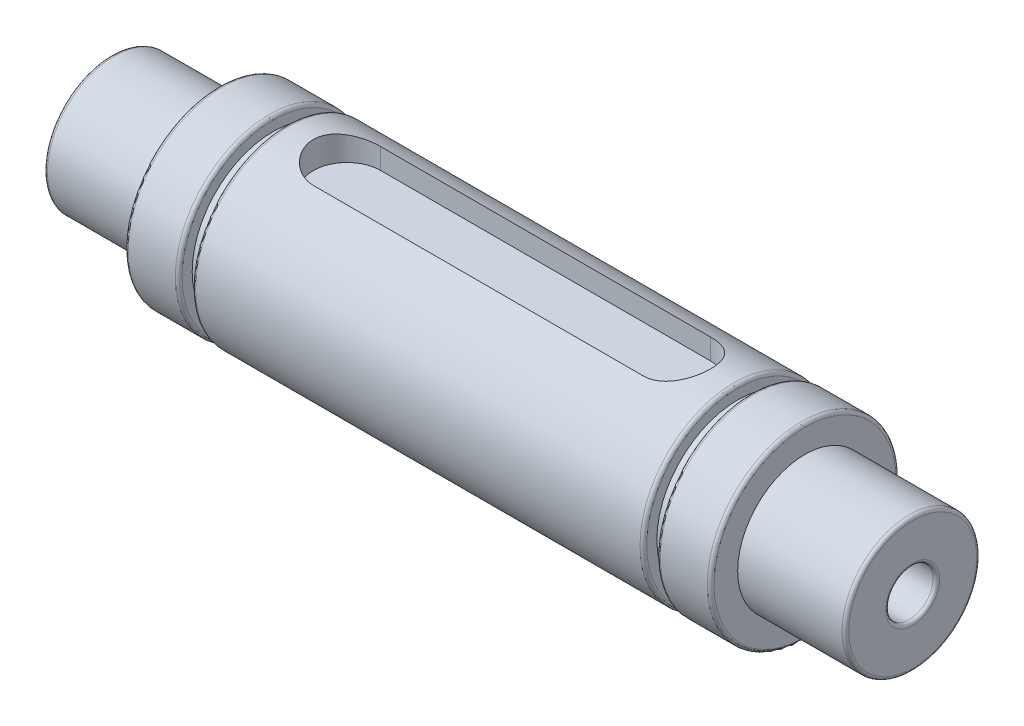
SolidWorks part; units mm, degrees
ref_plane "Front Plane" through (0, 0, 0) normal (0, 0, 1) x (1, 0, 0)
ref_plane "Top Plane" through (0, 0, 0) normal (0, 1, 0) x (1, 0, 0)
ref_plane "Right Plane" through (0, 0, 0) normal (1, 0, 0) x (0, 0, -1)
sketch "Sketch1" plane through (0, 0, 0) normal (0, 1, 0) x (1, 0, 0)
  line L0 (-23.6017, 0) -> (55.1984, 0) construction
sketch "Sketch3" plane through (0, 0, 0) normal (0, 1, 0) x (1, 0, 0)
  line L2 (-29.75, 5) -> (-21.75, 5)
  line L3 (-21.75, 5) -> (-21.75, 7)
  line L5 (21.75, 7) -> (21.75, 5)
  line L6 (21.75, 5) -> (29.75, 5)
  line L9 (-21.75, 7) -> (-17.75, 7)
  line L10 (-17.75, 7) -> (-17.75, 6)
  line L11 (-17.75, 6) -> (-16.75, 6)
  line L12 (-16.75, 6) -> (-16.75, 7)
  line L13 (-16.75, 7) -> (16.75, 7)
  line L14 (16.75, 7) -> (16.75, 6)
  line L15 (16.75, 6) -> (17.75, 6)
  line L16 (17.75, 6) -> (17.75, 7)
  line L17 (17.75, 7) -> (21.75, 7)
  line L18 (29.75, 5) -> (29.75, 1.75)
  line L19 (29.75, 1.75) -> (23.25, 1.75)
  line L20 (23.25, 1.75) -> (23.25, 0)
  line L21 (-29.75, 5) -> (-29.75, 1.75)
  line L22 (-29.75, 1.75) -> (-23.25, 1.75)
  line L23 (-23.25, 1.75) -> (-23.25, 0)
  line L24 (-200023.6017, 0) -> (200055.1984, 0) construction
  line L25 (-23.25, 0) -> (23.25, 0)
  dimension "D1" = 59.5
  dimension "D2" = 7
  dimension "D3" = 8
  dimension "D4" = 5
  dimension "D5" = 1
  dimension "D6" = 4
  dimension "D7" = 1
  dimension "D8" = 1.75
  dimension "D9" = 6.5
revolve "Revolve1" add sketch "Sketch3" angle 360 about L0
fillet "Fillet1" radius 0.25 10 edges at (29.75, 0, 1.75) (-29.75, 0, 1.75) (-29.75, 0, 5) (-21.75, 0, 7) (-16.75, 0, 7) (-17.75, 0, 7) (17.75, 0, 7) (16.75, 0, 7) (21.75, 0, 7) (29.75, 0, 5)
fillet "Fillet2" radius 1.5 2 edges at (-23.25, 0, 1.75) (23.25, 0, 1.75)
ref_plane "Plane1" through (0, 7, 0) normal (0, 1, 0) x (1, 0, 0)
sketch "Sketch4" plane through (0, 7, 0) normal (0, 1, 0) x (1, 0, 0)
  line L0 (-12.25, 0) -> (12.25, 0) construction
  line L1 (-12.25, -2.5) -> (12.25, -2.5)
  line L2 (12.25, 2.5) -> (-12.25, 2.5)
  line L3 (-12.25, 0) -> (-14.75, 0) construction
  line L4 (-14.75, 0) -> (-29.75, 0) construction
  line L5 (-29.75, 2) -> (-29.75, -2) construction
  line L6 (12.25, 0) -> (14.75, 0) construction
  line L7 (14.75, 0) -> (29.75, 0) construction
  line L8 (29.75, -4.75) -> (29.75, 4.75) construction
  circle A0 centre (-12.25, 0) radius 2.5
  circle A1 centre (12.25, 0) radius 2.5
  dimension "D1" = 5
  dimension "D2" = 15
extrude "Cut-Extrude1" cut sketch "Sketch4" against normal blind 2 contours A1 L2 A0 L1 | A0 | A1
